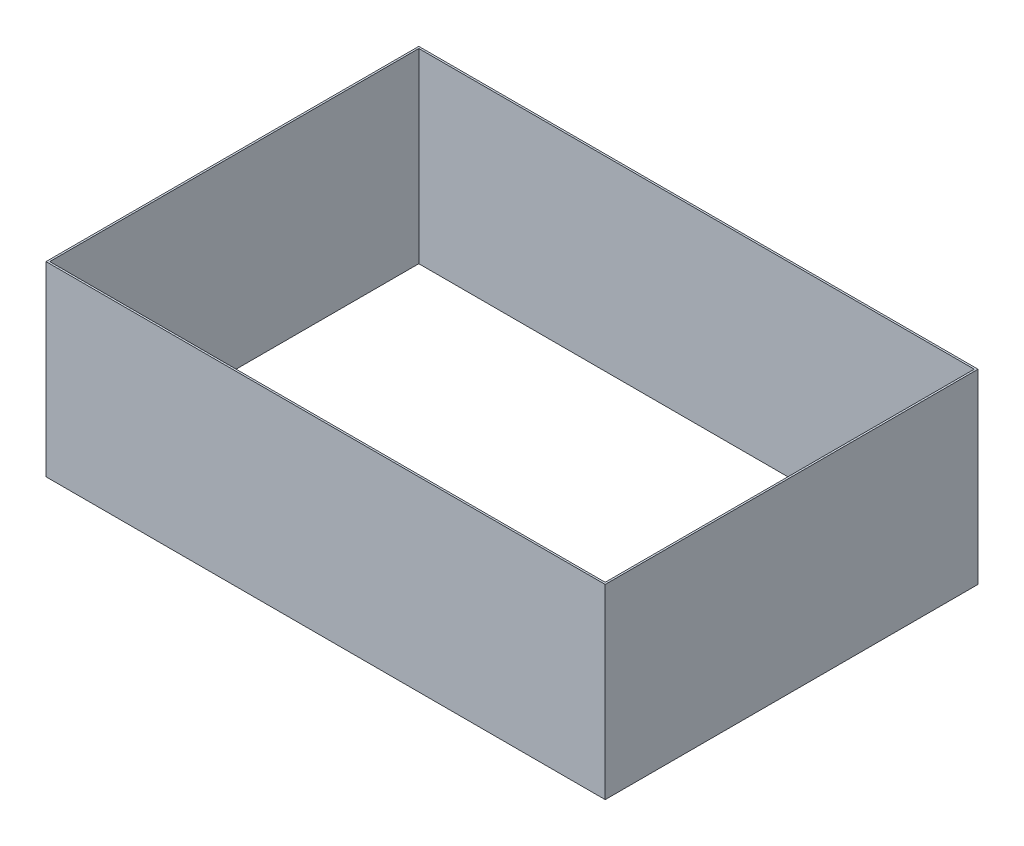
SolidWorks part; units mm, degrees
material "Клен"
ref_plane "Спереди XY" through (0, 0, 0) normal (0, 0, 1) x (1, 0, 0)
ref_plane "Сверху XZ" through (0, 0, 0) normal (0, 1, 0) x (1, 0, 0)
ref_plane "Справа ZY" through (0, 0, 0) normal (1, 0, 0) x (0, 0, -1)
sketch "Эскиз1" plane through (0, 0, 0) normal (0, 1, 0) x (1, 0, 0)
  line L1 (150, 100) -> (-150, 100)
  line L2 (150, 100) -> (150, -100)
  line L3 (150, -100) -> (-150, -100)
  line L4 (-150, 100) -> (-150, -100)
  line L5 (150, 100) -> (-150, -100) construction
  line L6 (150, -100) -> (-150, 100) construction
  point P0 (0, 0)
  dimension "D1" = 200
  dimension "D2" = 300
extrude "Вытянуть-Тонкостенный1" add sketch "Эскиз1" along normal blind 100 thin thin type one direction reverse wall 1
